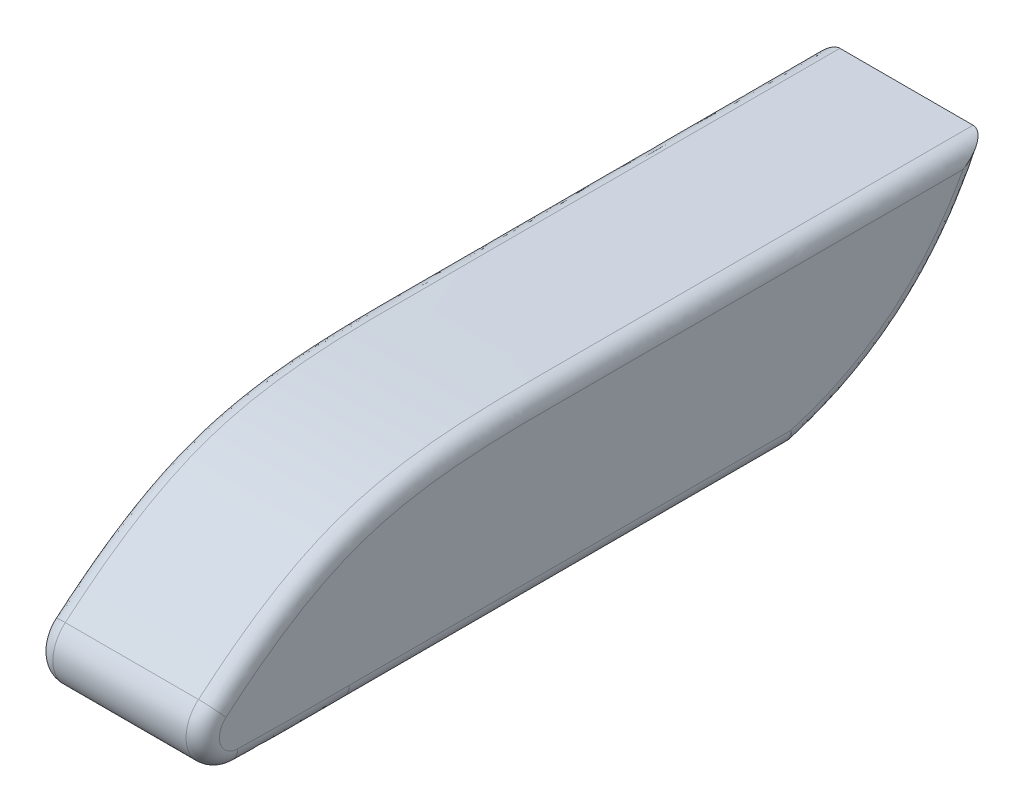
SolidWorks part; units mm, degrees
ref_plane "Front Plane" through (0, 0, 0) normal (0, 0, 1) x (1, 0, 0)
ref_plane "Top Plane" through (0, 0, 0) normal (0, 1, 0) x (1, 0, 0)
ref_plane "Right Plane" through (0, 0, 0) normal (1, 0, 0) x (0, 0, -1)
sketch "Sketch1" plane through (0, 0, 0) normal (0, 0, 1) x (1, 0, 0)
  line L1 (-69.8953, 71.8586) -> (80.1047, 71.8586)
  line L2 (-69.8953, 71.8586) -> (-69.8953, -53.1414)
  line L3 (-69.8953, -53.1414) -> (80.1047, -53.1414)
  line L4 (80.1047, 71.8586) -> (80.1047, -53.1414)
  dimension "D1" = 150
  dimension "D2" = 125
extrude "Boss-Extrude1" add sketch "Sketch1" along normal blind 400
sketch "Sketch2" plane through (80.1047, 0, 0) normal (1, 0, 0) x (0, 0, -1)
  line L0 (-400, -53.1414) -> (0, -53.1414)
  line L1 (-400, 71.8586) -> (0, 71.8586) construction
  line L2 (-199.6293, 71.8586) -> (-199.6293, 102.8586) construction
  line L3 (0.1253, 91.8586) -> (264, 91.8586) construction
  line L4 (264, 91.8586) -> (264, 71.8586) construction
  line L5 (264, 71.8586) -> (0, 71.8586) construction
  line L7 (416.4, -13.1414) -> (111.6, -13.1414) construction
  line L8 (416.4, -13.1414) -> (416.4, -43.1414) construction
  line L9 (416.4, -43.1414) -> (111.6, -43.1414) construction
  line L10 (111.6, -13.1414) -> (111.6, -43.1414) construction
  line L11 (281.6, 26.8586) -> (246.4, 26.8586) construction
  line L12 (281.6, 26.8586) -> (281.6, -43.1414) construction
  line L13 (281.6, -43.1414) -> (246.4, -43.1414) construction
  line L14 (246.4, 26.8586) -> (246.4, -43.1414) construction
  line L15 (275.6008, 71.8586) -> (252.3992, 71.8586) construction
  line L16 (275.6008, 71.8586) -> (275.6008, 26.8586) construction
  line L17 (275.6008, 26.8586) -> (252.3992, 26.8586) construction
  line L18 (252.3992, 71.8586) -> (252.3992, 26.8586) construction
  arc A0 (-520.8832, 3.7395) -> (-500.8185, -52.4442) centre (-500.1558, -20.5329) ccw
  spline S0 degree 3 poles (-520.8832, 3.7395) (-484.2811, 34.9957) (-387.3095, 103.2376) (-208.339, 102.7602) (-17.5904, 102.8962) (108.7463, 102.8418) (176.9642, 102.8586) knots 0 0 0 0 0.198054 0.477755 0.715159 1 1 1 1
  spline S1 degree 3 poles (-400, -53.1414) (-455.5471, -53.1414) (-454.1863, -53.4126) (-500.8185, -52.4442) knots 0 0 0 0 1 1 1 1
  spline S2 degree 2 poles (0, -53.1414) (122.2883, -18.619) (176.9642, 102.8586) knots 0 0 0 1 1 1
  point P11 (-503.8826, 16.2588)
  point P16 (264, 91.8586)
  point P17 (-200, 71.8586)
  point P26 (264, -43.1414)
  point P27 (264, -13.1414)
  point P28 (264, -43.1414)
  point P36 (-503.8681, -43.1414)
  point P41 (264, 71.8586)
  point P42 (-465.6402, -48.5454)
  point P43 (0, 0)
  point P44 (-400, 79.7929)
  point P45 (-520.8832, 3.7395)
  dimension "D1" = 464
  dimension "D2" = 31
  dimension "D3" = 20
  dimension "D4" = 304.8
  dimension "D5" = 30
  dimension "D6" = 70
  dimension "D7" = 35.2
  dimension "D8" = 45
extrude "Boss-Extrude2" add sketch "Sketch2" against normal up to surface (150 mm away) up to face at (-69.8953, 9.3586, 200)
fillet "Fillet1" radius 15 11 edges at (-69.8953, -31.2676, 530.2147) (80.1047, -31.2676, 530.2147) (80.1047, -53.1414, 200) (-69.8953, -53.1414, 200) (5.1047, -53.1414, 0)
